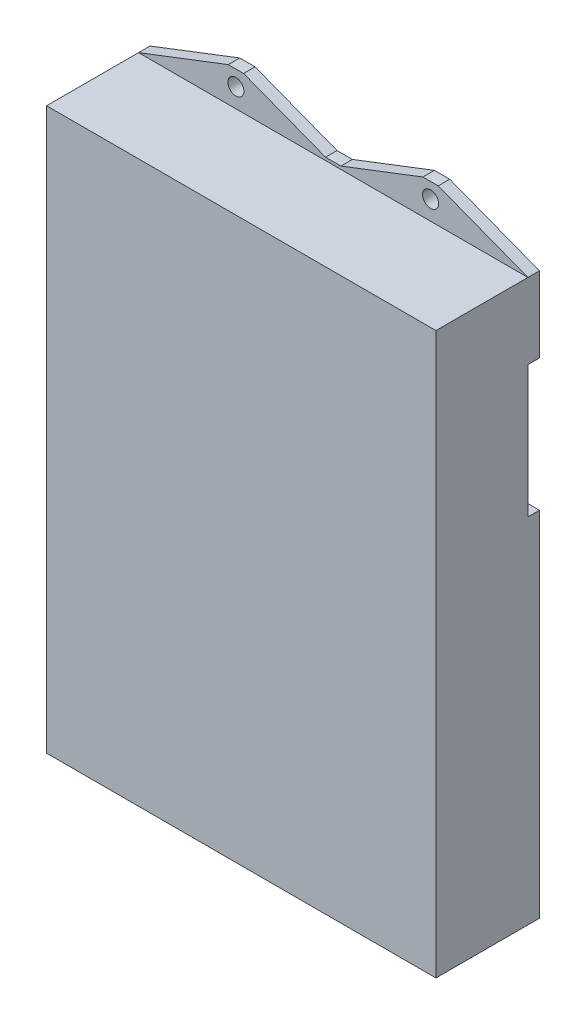
SolidWorks part; units mm, degrees
ref_plane "Plan de face" through (0, 0, 0) normal (0, 0, 1) x (1, 0, 0)
ref_plane "Plan de dessus" through (0, 0, 0) normal (0, 1, 0) x (1, 0, 0)
ref_plane "Plan de droite" through (0, 0, 0) normal (1, 0, 0) x (0, 0, -1)
sketch "Esquisse1" plane through (0, 0, 0) normal (0, 0, 1) x (1, 0, 0)
  line L0 (-50.8, -82.15) -> (-50.8, 82.15) construction
  line L1 (-50.8, 82.15) -> (50.8, 82.15) construction
  line L2 (50.8, 82.15) -> (50.8, -82.15) construction
  line L3 (50.8, -82.15) -> (-50.8, -82.15) construction
  line L4 (0, 0) -> (50.8, 0) construction
  line L5 (0, 0) -> (0, 82.15) construction
  line L6 (-50.8, 73.15) -> (-27.4, 82.15)
  line L7 (-27.4, 82.15) -> (-23.4, 82.15)
  line L8 (-23.4, 82.15) -> (-2, 73.9192)
  line L9 (-2, 73.9192) -> (2, 73.9192)
  line L10 (50.8, 73.15) -> (27.4, 82.15)
  line L11 (27.4, 82.15) -> (23.4, 82.15)
  line L12 (23.4, 82.15) -> (2, 73.9192)
  line L13 (50.8, -73.15) -> (27.4, -82.15)
  line L14 (27.4, -82.15) -> (23.4, -82.15)
  line L15 (23.4, -82.15) -> (2, -73.9192)
  line L16 (-2, -73.9192) -> (2, -73.9192)
  line L17 (-23.4, -82.15) -> (-2, -73.9192)
  line L18 (-27.4, -82.15) -> (-23.4, -82.15)
  line L19 (-50.8, -73.15) -> (-27.4, -82.15)
  line L20 (-25.4, 78.15) -> (-25.4, 87.1997) construction
  line L21 (-50.8, 73.15) -> (-50.8, 53.45)
  line L22 (-50.8, 53.45) -> (-43.2, 53.45)
  line L23 (-43.2, 53.45) -> (-43.2, 19.05)
  line L25 (-50.8, 19.05) -> (-50.8, -73.15)
  line L26 (50.8, 73.15) -> (50.8, 53.45)
  line L27 (50.8, 53.45) -> (43.2, 53.45)
  line L28 (43.2, 53.45) -> (43.2, 19.05)
  line L31 (-50.8, 19.05) -> (-43.2, 19.05)
  line L32 (43.2, 19.05) -> (50.8, 19.05)
  line L33 (50.8, 19.05) -> (50.8, -73.15)
  circle A0 centre (-25.4, -78.15) radius 2.1
  circle A1 centre (25.4, -78.15) radius 2.1
  circle A2 centre (-25.4, 78.15) radius 2.1
  circle A3 centre (25.4, 78.15) radius 2.1
  circle A4 centre (-48.1, -69.85) radius 1.5
  circle A5 centre (48.1, -69.85) radius 1.5
  circle A6 centre (-48.1, 69.85) radius 1.5
  circle A7 centre (48.1, 69.85) radius 1.5
  point P7 (0, 82.15)
  point P9 (50.8, 0)
  dimension "D5" = 4.2
  dimension "D6" = 3
  dimension "D1" = 101.6
  dimension "D2" = 164.3
  dimension "D3" = 50.8
  dimension "D4" = 4
  dimension "D7" = 96.2
  dimension "D8" = 12.3
  dimension "D9" = 9
  dimension "D10" = 4
  dimension "D11" = 19.7
  dimension "D12" = 7.6
  dimension "D13" = 34.4
extrude "Boss.-Extru.1" add sketch "Esquisse1" along normal blind 3
sketch "Esquisse2" plane through (0, 0, 3) normal (0, 0, 1) x (1, 0, 0)
  line L1 (-50.8, 73.15) -> (50.8, 73.15)
  line L2 (-50.8, 73.15) -> (-50.8, -73.15)
  line L3 (-50.8, -73.15) -> (50.8, -73.15)
  line L4 (50.8, 73.15) -> (50.8, -73.15)
extrude "Boss.-Extru.2" add sketch "Esquisse2" along normal blind 24
